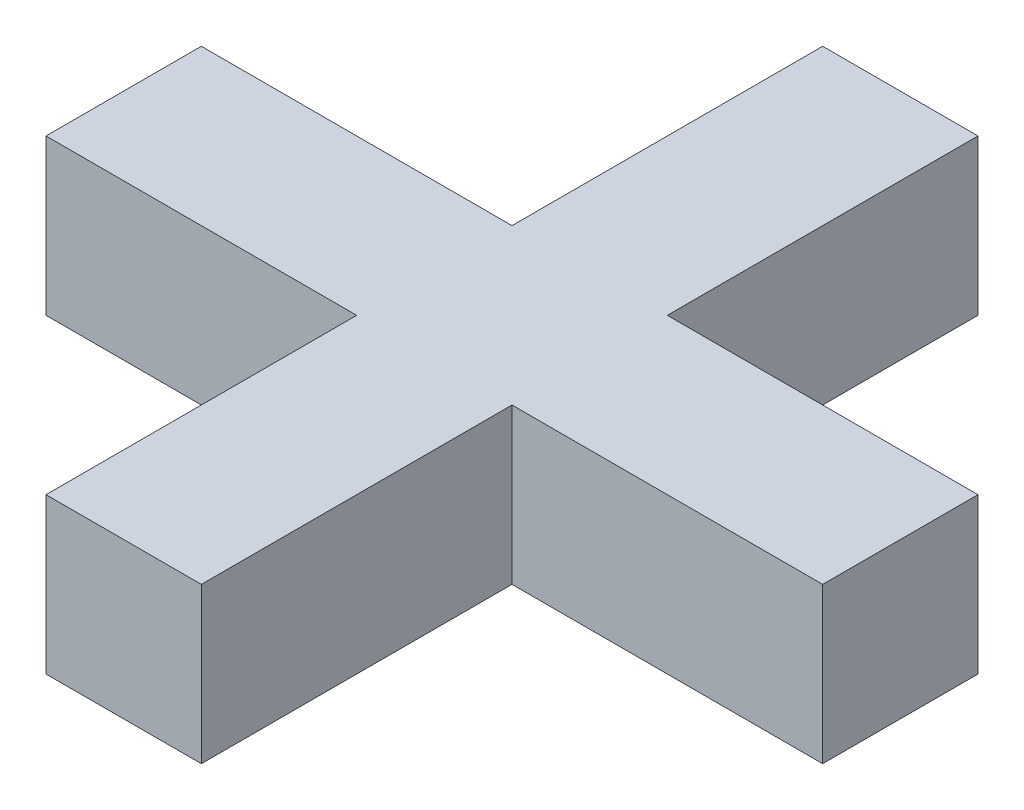
SolidWorks part; units mm, degrees
ref_plane "前基準面" through (0, 0, 0) normal (0, 0, 1) x (1, 0, 0)
ref_plane "上基準面" through (0, 0, 0) normal (0, 1, 0) x (1, 0, 0)
ref_plane "右基準面" through (0, 0, 0) normal (1, 0, 0) x (0, 0, -1)
sketch "草圖1" plane through (0, 0, 0) normal (0, 1, 0) x (1, 0, 0)
  line L1 (-100, -500) -> (100, -500)
  line L2 (-100, -500) -> (-100, 500)
  line L3 (-100, 500) -> (100, 500)
  line L4 (100, -500) -> (100, 500)
  line L5 (-100, -500) -> (100, 500) construction
  line L6 (-100, 500) -> (100, -500) construction
  line L7 (-500, 100) -> (500, 100)
  line L8 (-500, 100) -> (-500, -100)
  line L9 (-500, -100) -> (500, -100)
  line L10 (500, 100) -> (500, -100)
  line L11 (-500, 100) -> (500, -100) construction
  line L12 (-500, -100) -> (500, 100) construction
  point P0 (0, 0)
  point P6 (0, 0)
  dimension "D1" = 200
  dimension "D2" = 1000
extrude "填料-伸長1" add sketch "草圖1" along normal blind 200 contours L8 L9 L2 L7 | L2 L9 L4 L7 | L10 L7 L4 L9 | L9 L2 L1 L4 | L2 L7 L4 L3
